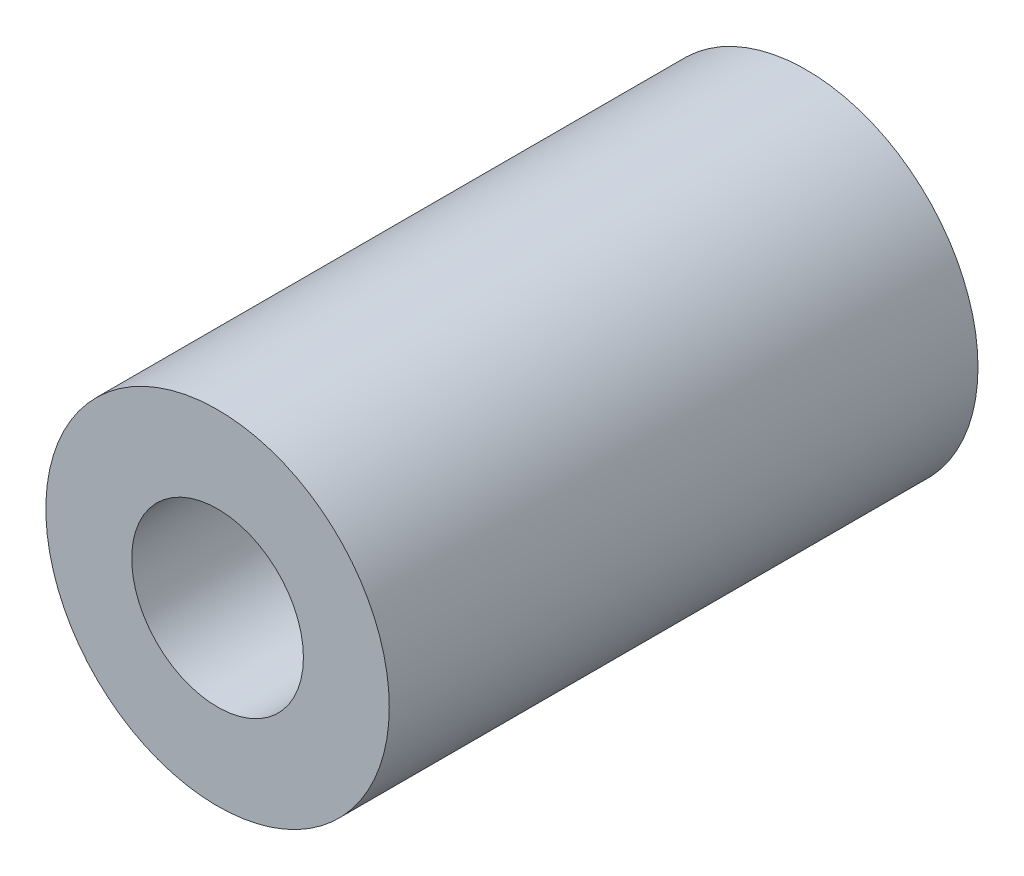
SolidWorks part; units mm, degrees
ref_plane "前视基准面" through (0, 0, 0) normal (0, 0, 1) x (1, 0, 0)
ref_plane "上视基准面" through (0, 0, 0) normal (0, 1, 0) x (1, 0, 0)
ref_plane "右视基准面" through (0, 0, 0) normal (1, 0, 0) x (0, 0, -1)
sketch "草图1" plane through (0, 0, 0) normal (0, 0, 1) x (1, 0, 0)
  circle A0 centre (0, 0) radius 3.5
  circle A1 centre (0, 0) radius 1.75
  dimension "D1" = 3.5
  dimension "D2" = 7
extrude "凸台-拉伸1" add sketch "草图1" along normal blind 12
